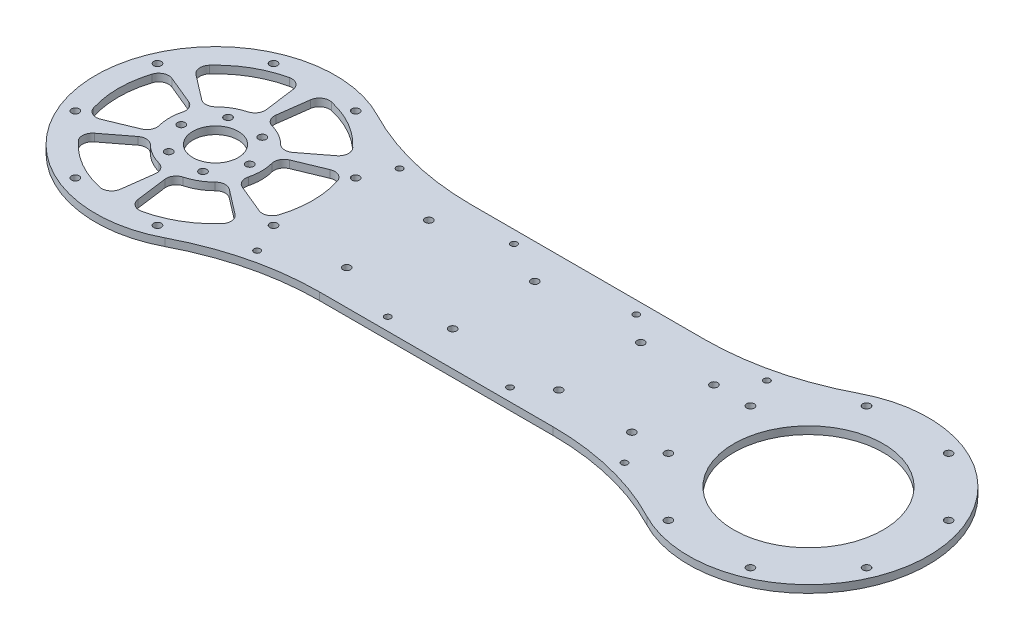
SolidWorks part; units mm, degrees
material "Hexcel AS4C (3000 丝)"
ref_plane "前视基准面" through (0, 0, 0) normal (0, 0, 1) x (1, 0, 0)
ref_plane "上视基准面" through (0, 0, 0) normal (0, 1, 0) x (1, 0, 0)
ref_plane "右视基准面" through (0, 0, 0) normal (1, 0, 0) x (0, 0, -1)
sketch "草图1" plane through (0, 0, 0) normal (0, 1, 0) x (1, 0, 0)
  line L0 (0, 0) -> (235, 0) construction
  line L1 (71.2712, 30) -> (163.7288, 30)
  line L2 (251.264, 39.2649) -> (218.736, 39.2649) construction
  line L3 (218.736, 39.2649) -> (195.7351, 16.264) construction
  line L4 (195.7351, 16.264) -> (195.7351, -16.264) construction
  line L5 (195.7351, -16.264) -> (218.736, -39.2649) construction
  line L6 (218.736, -39.2649) -> (251.264, -39.2649) construction
  line L7 (251.264, -39.2649) -> (274.2649, -16.264) construction
  line L8 (274.2649, -16.264) -> (274.2649, 16.264) construction
  line L9 (274.2649, 16.264) -> (251.264, 39.2649) construction
  line L18 (16.264, -39.2649) -> (39.2649, -16.264) construction
  line L19 (39.2649, -16.264) -> (39.2649, 16.264) construction
  line L20 (39.2649, 16.264) -> (16.264, 39.2649) construction
  line L21 (16.264, 39.2649) -> (-16.264, 39.2649) construction
  line L22 (-16.264, 39.2649) -> (-39.2649, 16.264) construction
  line L23 (-39.2649, 16.264) -> (-39.2649, -16.264) construction
  line L24 (-39.2649, -16.264) -> (-16.264, -39.2649) construction
  line L25 (-16.264, -39.2649) -> (16.264, -39.2649) construction
  line L26 (71.2712, -30) -> (163.7288, -30)
  line L27 (22, 42.0981) -> (22, -42.0981) construction
  line L28 (213, 42.0981) -> (213, -42.0981) construction
  line L30 (6.7839, -11.75) -> (13.5677, 0) construction
  line L31 (13.5677, 0) -> (6.7839, 11.75) construction
  line L32 (6.7839, 11.75) -> (-6.7839, 11.75) construction
  line L33 (-6.7839, 11.75) -> (-13.5677, 0) construction
  line L34 (-13.5677, 0) -> (-6.7839, -11.75) construction
  line L35 (-6.7839, -11.75) -> (6.7839, -11.75) construction
  circle A0 centre (0, 0) radius 9
  circle A1 centre (235, 0) radius 29.6
  circle A3 centre (235, 0) radius 42.5 construction
  circle A4 centre (218.736, 39.2649) radius 1.5
  circle A5 centre (251.264, 39.2649) radius 1.5
  circle A6 centre (274.2649, 16.264) radius 1.5
  circle A7 centre (195.7351, 16.264) radius 1.5
  circle A8 centre (195.7351, -16.264) radius 1.5
  circle A9 centre (274.2649, -16.264) radius 1.5
  circle A10 centre (251.264, -39.2649) radius 1.5
  circle A11 centre (218.736, -39.2649) radius 1.5
  circle A12 centre (235, 0) radius 47.5 construction
  circle A13 centre (0, 0) radius 47.5 construction
  circle A14 centre (0, 0) radius 42.5 construction
  arc A15 (22, 42.0981) -> (22, -42.0981) centre (0, 0) ccw
  arc A16 (213, 42.0981) -> (213, -42.0981) centre (235, 0) cw
  arc A17 (22, 42.0981) -> (71.2712, 30) centre (71.2712, 136.381) ccw
  arc A18 (22, -42.0981) -> (71.2712, -30) centre (71.2712, -136.381) cw
  arc A19 (213, 42.0981) -> (163.7288, 30) centre (163.7288, 136.381) cw
  arc A20 (163.7288, -30) -> (213, -42.0981) centre (163.7288, -136.381) cw
  circle A21 centre (-16.264, 39.2649) radius 1.5
  circle A22 centre (16.264, 39.2649) radius 1.5
  circle A23 centre (39.2649, 16.264) radius 1.5
  circle A24 centre (39.2649, -16.264) radius 1.5
  circle A25 centre (16.264, -39.2649) radius 1.5
  circle A26 centre (-16.264, -39.2649) radius 1.5
  circle A27 centre (-39.2649, -16.264) radius 1.5
  circle A28 centre (-39.2649, 16.264) radius 1.5
  circle A29 centre (0, 0) radius 11.75 construction
  circle A30 centre (-6.7839, 11.75) radius 1.5
  circle A31 centre (6.7839, 11.75) radius 1.5
  circle A32 centre (13.5677, 0) radius 1.5
  circle A33 centre (6.7839, -11.75) radius 1.5
  circle A34 centre (-13.5677, 0) radius 1.5
  circle A35 centre (-6.7839, -11.75) radius 1.5
  dimension "D1" = 18
  dimension "D3" = 59.2
  dimension "D4" = 85
  dimension "D5" = 3
  dimension "D6" = 95
  dimension "D7" = 85
  dimension "D11" = 3
  dimension "D12" = 23.5
  dimension "D13" = 3
  dimension "D2" = 235
  dimension "D8" = 60
  dimension "D9" = 22
  dimension "D10" = 22
extrude "凸台-拉伸1" add sketch "草图1" along normal blind 3
sketch "草图2" plane through (0, 3, 0) normal (0, 1, 0) x (1, 0, 0)
  line L0 (0, 0) -> (244.9307, 0) construction
  line L1 (71.2712, 30) -> (163.7288, 30) construction
  line L2 (71.2712, 25) -> (163.7288, 25) construction
  circle A0 centre (93.2712, 25) radius 1.25
  circle A1 centre (141.7288, 25) radius 1.25
  circle A2 centre (190.2885, 28.213) radius 1.25
  circle A3 centre (44.7115, 28.213) radius 1.25
  arc A5 (22, 42.0981) -> (71.2712, 30) centre (71.2712, 136.381) ccw construction
  arc A6 (163.7288, 30) -> (213, 42.0981) centre (163.7288, 136.381) ccw construction
  arc A8 (19.6842, 37.6667) -> (71.2712, 25) centre (71.2712, 136.381) ccw construction
  arc A9 (163.7288, 25) -> (215.3158, 37.6667) centre (163.7288, 136.381) ccw construction
  circle A10 centre (44.7115, -28.213) radius 1.25
  circle A11 centre (93.2712, -25) radius 1.25
  circle A12 centre (190.2885, -28.213) radius 1.25
  circle A13 centre (141.7288, -25) radius 1.25
  dimension "D2" = 2.5
  dimension "D1" = 5
  dimension "D3" = 22
  dimension "D4" = 22
extrude "切除-拉伸1" cut sketch "草图2" against normal through all both and the other way through all
sketch "草图3" plane through (0, 3, 0) normal (0, 1, 0) x (1, 0, 0)
  line L2 (31.3704, 14.0764) -> (19.9859, 9.3608)
  line L3 (19.9859, -9.3608) -> (31.3704, -14.0764)
  line L4 (31.3704, 14.0764) -> (19.9859, 9.3608)
  line L5 (19.9859, -9.3608) -> (31.3704, -14.0764)
  line L6 (-3.4947, -34.2058) -> (-1.8862, -21.9887)
  line L7 (-18.0997, -12.6279) -> (-27.8758, -20.1294)
  line L8 (-3.4947, -34.2058) -> (-1.8862, -21.9887)
  line L9 (-18.0997, -12.6279) -> (-27.8758, -20.1294)
  line L10 (-27.8758, 20.1294) -> (-18.0997, 12.6279)
  line L11 (-1.8862, 21.9887) -> (-3.4947, 34.2058)
  line L12 (-27.8758, 20.1294) -> (-18.0997, 12.6279)
  line L13 (-1.8862, 21.9887) -> (-3.4947, 34.2058)
  line L14 (-31.3704, -14.0764) -> (-19.9859, -9.3608)
  line L15 (-19.9859, 9.3608) -> (-31.3704, 14.0764)
  line L16 (-31.3704, -14.0764) -> (-19.9859, -9.3608)
  line L17 (-19.9859, 9.3608) -> (-31.3704, 14.0764)
  line L18 (27.8758, -20.1294) -> (18.0997, -12.6279)
  line L19 (1.8862, -21.9887) -> (3.4947, -34.2058)
  line L20 (27.8758, -20.1294) -> (18.0997, -12.6279)
  line L21 (1.8862, -21.9887) -> (3.4947, -34.2058)
  line L22 (3.4947, 34.2058) -> (1.8862, 21.9887)
  line L23 (18.0997, 12.6279) -> (27.8758, 20.1294)
  line L24 (3.4947, 34.2058) -> (1.8862, 21.9887)
  line L25 (18.0997, 12.6279) -> (27.8758, 20.1294)
  circle A1 centre (12, -6.9282) radius 3
  circle A2 centre (12, -6.9282) radius 3
  circle A3 centre (-12, -6.9282) radius 3
  circle A4 centre (-12, -6.9282) radius 3
  circle A5 centre (0, 13.8564) radius 3
  arc A6 (19.9859, 9.3608) -> (17.6485, 4.6468) centre (21.5167, 5.6653) ccw
  arc A7 (36.7158, 11.5845) -> (31.3704, 14.0764) centre (32.9012, 10.3809) ccw
  arc A8 (36.7158, -11.5845) -> (36.7158, 11.5845) centre (0, 0) ccw
  arc A9 (31.3704, -14.0764) -> (36.7158, -11.5845) centre (32.9012, -10.3809) ccw
  arc A10 (17.6485, -4.6468) -> (19.9859, -9.3608) centre (21.5167, -5.6653) ccw
  arc A11 (17.6485, -4.6468) -> (17.6485, 4.6468) centre (0, 0) ccw
  arc A12 (19.9859, 9.3608) -> (17.6485, 4.6468) centre (21.5167, 5.6653) ccw
  arc A13 (36.7158, 11.5845) -> (31.3704, 14.0764) centre (32.9012, 10.3809) ccw
  arc A14 (36.7158, -11.5845) -> (36.7158, 11.5845) centre (0, 0) ccw
  arc A15 (31.3704, -14.0764) -> (36.7158, -11.5845) centre (32.9012, -10.3809) ccw
  arc A16 (17.6485, -4.6468) -> (19.9859, -9.3608) centre (21.5167, -5.6653) ccw
  arc A17 (17.6485, -4.6468) -> (17.6485, 4.6468) centre (0, 0) ccw
  arc A18 (-1.8862, -21.9887) -> (-4.8, -17.6075) centre (-5.852, -21.4666) ccw
  arc A19 (-8.3254, -37.5891) -> (-3.4947, -34.2058) centre (-7.4604, -33.6837) ccw
  arc A20 (-28.3904, -26.0045) -> (-8.3254, -37.5891) centre (0, 0) ccw
  arc A21 (-27.8758, -20.1294) -> (-28.3904, -26.0045) centre (-25.4407, -23.3028) ccw
  arc A22 (-12.8485, -12.9606) -> (-18.0997, -12.6279) centre (-15.6646, -15.8013) ccw
  arc A23 (-12.8485, -12.9606) -> (-4.8, -17.6075) centre (0, 0) ccw
  arc A24 (-1.8862, -21.9887) -> (-4.8, -17.6075) centre (-5.852, -21.4666) ccw
  arc A25 (-8.3254, -37.5891) -> (-3.4947, -34.2058) centre (-7.4604, -33.6837) ccw
  arc A26 (-28.3904, -26.0045) -> (-8.3254, -37.5891) centre (0, 0) ccw
  arc A27 (-27.8758, -20.1294) -> (-28.3904, -26.0045) centre (-25.4407, -23.3028) ccw
  arc A28 (-12.8485, -12.9606) -> (-18.0997, -12.6279) centre (-15.6646, -15.8013) ccw
  arc A29 (-12.8485, -12.9606) -> (-4.8, -17.6075) centre (0, 0) ccw
  circle A30 centre (0, 13.8564) radius 3
  circle A31 centre (-13.5677, 0) radius 2.5
  circle A32 centre (-13.5677, 0) radius 2.5
  circle A33 centre (-6.7839, -11.75) radius 2.5
  circle A34 centre (-6.7839, -11.75) radius 2.5
  circle A35 centre (6.7839, -11.75) radius 2.5
  circle A36 centre (6.7839, -11.75) radius 2.5
  circle A37 centre (13.5677, 0) radius 2.5
  circle A38 centre (13.5677, 0) radius 2.5
  circle A39 centre (6.7839, 11.75) radius 2.5
  circle A40 centre (6.7839, 11.75) radius 2.5
  circle A41 centre (-6.7839, 11.75) radius 2.5
  circle A42 centre (-6.7839, 11.75) radius 2.5
  circle A43 centre (0, 0) radius 10
  circle A44 centre (0, 0) radius 10
  circle A45 centre (-39.2649, 16.264) radius 2.5
  circle A46 centre (-39.2649, 16.264) radius 2.5
  circle A47 centre (-39.2649, -16.264) radius 2.5
  circle A48 centre (-39.2649, -16.264) radius 2.5
  circle A49 centre (-16.264, -39.2649) radius 2.5
  circle A50 centre (-16.264, -39.2649) radius 2.5
  circle A51 centre (16.264, -39.2649) radius 2.5
  circle A52 centre (16.264, -39.2649) radius 2.5
  circle A53 centre (39.2649, -16.264) radius 2.5
  circle A54 centre (39.2649, -16.264) radius 2.5
  circle A55 centre (39.2649, 16.264) radius 2.5
  circle A56 centre (39.2649, 16.264) radius 2.5
  circle A57 centre (16.264, 39.2649) radius 2.5
  circle A58 centre (16.264, 39.2649) radius 2.5
  circle A59 centre (-16.264, 39.2649) radius 2.5
  circle A60 centre (-16.264, 39.2649) radius 2.5
  arc A66 (-18.0997, 12.6279) -> (-12.8485, 12.9606) centre (-15.6646, 15.8013) ccw
  arc A67 (-28.3904, 26.0045) -> (-27.8758, 20.1294) centre (-25.4407, 23.3028) ccw
  arc A68 (-8.3254, 37.5891) -> (-28.3904, 26.0045) centre (0, 0) ccw
  arc A69 (-3.4947, 34.2058) -> (-8.3254, 37.5891) centre (-7.4604, 33.6837) ccw
  arc A70 (-4.8, 17.6075) -> (-1.8862, 21.9887) centre (-5.852, 21.4666) ccw
  arc A71 (-4.8, 17.6075) -> (-12.8485, 12.9606) centre (0, 0) ccw
  arc A72 (-18.0997, 12.6279) -> (-12.8485, 12.9606) centre (-15.6646, 15.8013) ccw
  arc A73 (-28.3904, 26.0045) -> (-27.8758, 20.1294) centre (-25.4407, 23.3028) ccw
  arc A74 (-8.3254, 37.5891) -> (-28.3904, 26.0045) centre (0, 0) ccw
  arc A75 (-3.4947, 34.2058) -> (-8.3254, 37.5891) centre (-7.4604, 33.6837) ccw
  arc A76 (-4.8, 17.6075) -> (-1.8862, 21.9887) centre (-5.852, 21.4666) ccw
  arc A77 (-4.8, 17.6075) -> (-12.8485, 12.9606) centre (0, 0) ccw
  arc A78 (-19.9859, -9.3608) -> (-17.6485, -4.6468) centre (-21.5167, -5.6653) ccw
  arc A79 (-36.7158, -11.5845) -> (-31.3704, -14.0764) centre (-32.9012, -10.3809) ccw
  arc A80 (-36.7158, 11.5845) -> (-36.7158, -11.5845) centre (0, 0) ccw
  arc A81 (-31.3704, 14.0764) -> (-36.7158, 11.5845) centre (-32.9012, 10.3809) ccw
  arc A82 (-17.6485, 4.6468) -> (-19.9859, 9.3608) centre (-21.5167, 5.6653) ccw
  arc A83 (-17.6485, 4.6468) -> (-17.6485, -4.6468) centre (0, 0) ccw
  arc A84 (-19.9859, -9.3608) -> (-17.6485, -4.6468) centre (-21.5167, -5.6653) ccw
  arc A85 (-36.7158, -11.5845) -> (-31.3704, -14.0764) centre (-32.9012, -10.3809) ccw
  arc A86 (-36.7158, 11.5845) -> (-36.7158, -11.5845) centre (0, 0) ccw
  arc A87 (-31.3704, 14.0764) -> (-36.7158, 11.5845) centre (-32.9012, 10.3809) ccw
  arc A88 (-17.6485, 4.6468) -> (-19.9859, 9.3608) centre (-21.5167, 5.6653) ccw
  arc A89 (-17.6485, 4.6468) -> (-17.6485, -4.6468) centre (0, 0) ccw
  arc A90 (18.0997, -12.6279) -> (12.8485, -12.9606) centre (15.6646, -15.8013) ccw
  arc A91 (28.3904, -26.0045) -> (27.8758, -20.1294) centre (25.4407, -23.3028) ccw
  arc A92 (8.3254, -37.5891) -> (28.3904, -26.0045) centre (0, 0) ccw
  arc A93 (3.4947, -34.2058) -> (8.3254, -37.5891) centre (7.4604, -33.6837) ccw
  arc A94 (4.8, -17.6075) -> (1.8862, -21.9887) centre (5.852, -21.4666) ccw
  arc A95 (4.8, -17.6075) -> (12.8485, -12.9606) centre (0, 0) ccw
  arc A96 (18.0997, -12.6279) -> (12.8485, -12.9606) centre (15.6646, -15.8013) ccw
  arc A97 (28.3904, -26.0045) -> (27.8758, -20.1294) centre (25.4407, -23.3028) ccw
  arc A98 (8.3254, -37.5891) -> (28.3904, -26.0045) centre (0, 0) ccw
  arc A99 (3.4947, -34.2058) -> (8.3254, -37.5891) centre (7.4604, -33.6837) ccw
  arc A100 (4.8, -17.6075) -> (1.8862, -21.9887) centre (5.852, -21.4666) ccw
  arc A101 (4.8, -17.6075) -> (12.8485, -12.9606) centre (0, 0) ccw
  arc A102 (1.8862, 21.9887) -> (4.8, 17.6075) centre (5.852, 21.4666) ccw
  arc A103 (8.3254, 37.5891) -> (3.4947, 34.2058) centre (7.4604, 33.6837) ccw
  arc A104 (28.3904, 26.0045) -> (8.3254, 37.5891) centre (0, 0) ccw
  arc A105 (27.8758, 20.1294) -> (28.3904, 26.0045) centre (25.4407, 23.3028) ccw
  arc A106 (12.8485, 12.9606) -> (18.0997, 12.6279) centre (15.6646, 15.8013) ccw
  arc A107 (12.8485, 12.9606) -> (4.8, 17.6075) centre (0, 0) ccw
  arc A108 (1.8862, 21.9887) -> (4.8, 17.6075) centre (5.852, 21.4666) ccw
  arc A109 (8.3254, 37.5891) -> (3.4947, 34.2058) centre (7.4604, 33.6837) ccw
  arc A110 (28.3904, 26.0045) -> (8.3254, 37.5891) centre (0, 0) ccw
  arc A111 (27.8758, 20.1294) -> (28.3904, 26.0045) centre (25.4407, 23.3028) ccw
  arc A112 (12.8485, 12.9606) -> (18.0997, 12.6279) centre (15.6646, 15.8013) ccw
  arc A113 (12.8485, 12.9606) -> (4.8, 17.6075) centre (0, 0) ccw
  dimension "D1" = 0
  dimension "D2" = 0
  dimension "D3" = 0
  dimension "D4" = 0
  dimension "D5" = 0
  dimension "D6" = 0
  dimension "D7" = 0
  dimension "D8" = 0
  dimension "D9" = 0
  dimension "D10" = 0
  dimension "D11" = 0
  dimension "D12" = 0
  dimension "D13" = 0
  dimension "D14" = 0
  dimension "D15" = 0
  dimension "D16" = 0
  dimension "D17" = 0
  dimension "D18" = 0
  dimension "D19" = 0
  dimension "D20" = 0
  dimension "D21" = 0
  dimension "D22" = 0
  dimension "D23" = 0
  dimension "D24" = 0
extrude "切除-拉伸2" cut sketch "草图3" against normal through all both and the other way through all contours A29 A28 L9 A27 A26 A25 L8 A24 | A89 A88 L17 A87 A86 A85 L16 A84 | A77 A76 L13 A75 A74 A73 L12 A72 | A113 A112 L25 A111 A110 A109 L24 A108 | A17 A16 L5 A15 A14 A13 L4 A12 | A101 A100 L21 A99 A98 A97 L20 A96
sketch "草图4" plane through (0, 3, 0) normal (0, 1, 0) x (1, 0, 0)
  line L0 (0, 0) -> (28.7724, 0) construction
  line L1 (39.2649, 16.264) -> (16.5252, 16.264) construction
  line L2 (10, 14) -> (188, 14) construction
  line L3 (10, 14) -> (10, -14) construction
  line L4 (10, -14) -> (188, -14) construction
  line L5 (188, 14) -> (188, -14) construction
  line L6 (10, 14) -> (188, -14) construction
  line L7 (10, -14) -> (188, 14) construction
  circle A0 centre (235, 0) radius 47 construction
  circle A2 centre (68.2649, 16.264) radius 1.5
  circle A3 centre (110.2649, 16.264) radius 1.5
  circle A4 centre (152.2649, 16.264) radius 1.5
  circle A5 centre (181.2649, 16.264) radius 1.5
  circle A6 centre (68.2649, -16.264) radius 1.5
  circle A7 centre (110.2649, -16.264) radius 1.5
  circle A8 centre (152.2649, -16.264) radius 1.5
  circle A9 centre (181.2649, -16.264) radius 1.5
  point P1 (99, 0)
  point P12 (39.2649, 16.264)
  dimension "D5" = 3
  dimension "D1" = 178
  dimension "D2" = 28
  dimension "D3" = 29
  dimension "D4" = 42
  dimension "D6" = 42
  dimension "D7" = 29
extrude "切除-拉伸3" cut sketch "草图4" against normal through all both and the other way through all
